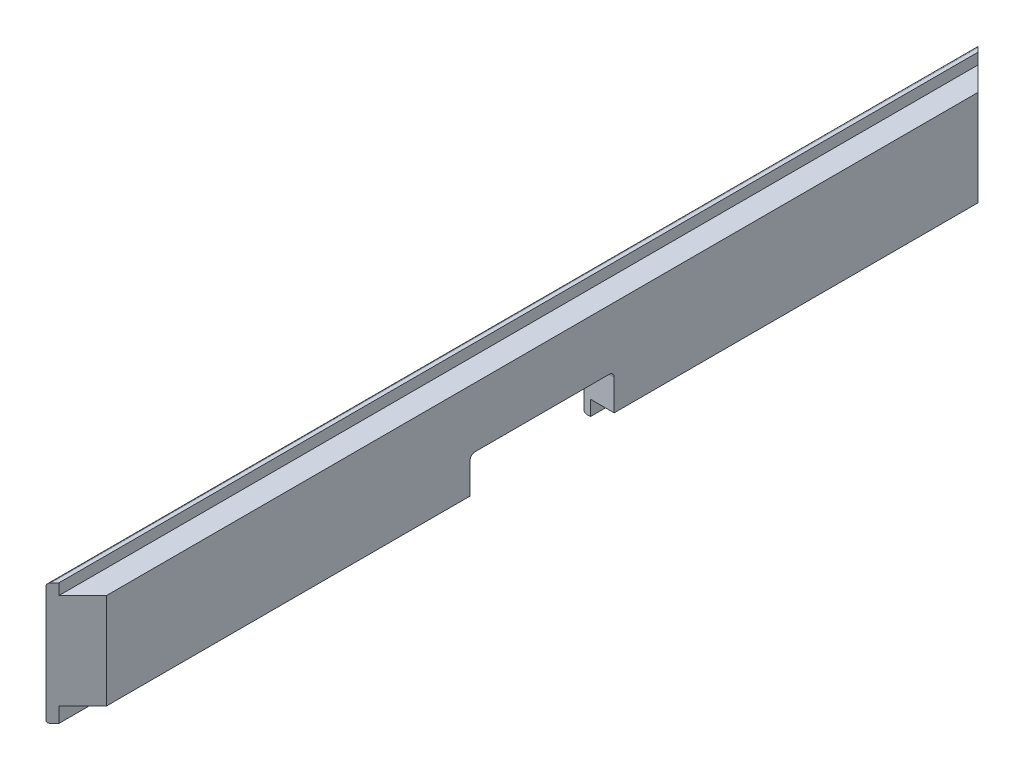
SolidWorks part; units mm, degrees
ref_plane "Front Plane" through (0, 0, 0) normal (0, 0, 1) x (1, 0, 0)
ref_plane "Top Plane" through (0, 0, 0) normal (0, 1, 0) x (1, 0, 0)
ref_plane "Right Plane" through (0, 0, 0) normal (1, 0, 0) x (0, 0, -1)
sketch "Sketch1" plane through (0, 0, 0) normal (0, 0, 1) x (1, 0, 0)
  line L1 (0, 0) -> (19.05, 0)
  line L2 (0, 0) -> (0, 77)
  line L3 (0, 77) -> (19.05, 77)
  line L4 (19.05, 0) -> (19.05, 77)
  line L5 (19.05, 77) -> (4.05, 77)
  line L6 (19.05, 77) -> (19.05, 70)
  line L7 (19.05, 70) -> (4.05, 70)
  line L8 (4.05, 77) -> (4.05, 70)
  line L9 (19.05, 0) -> (4.05, 0)
  line L10 (19.05, 0) -> (19.05, 9.525)
  line L11 (19.05, 9.525) -> (4.05, 9.525)
  line L12 (4.05, 0) -> (4.05, 9.525)
  dimension "D3" = 15
  dimension "D4" = 9.525
  dimension "D5" = 7
  dimension "D1" = 77
  dimension "D2" = 19.05
extrude "Boss-Extrude1" add sketch "Sketch1" along normal mid plane 589.1 contours L1 L12 L11 L4 L7 L8 L3 L2
fillet "Fillet1" radius 1.5875 2 edges at (0, 0, 0) (0, 77, 0)
sketch "Sketch2" plane through (0, 77, 0) normal (0, 1, 0) x (1, 0, 0)
  line L4 (0, 294.55) -> (19.05, 275.5)
  line L5 (19.05, 275.5) -> (19.05, 294.55)
  line L6 (19.05, 294.55) -> (0, 294.55)
  line L7 (-10.4775, 0) -> (10.4775, 0) construction
  line L9 (19.05, 275.5) -> (19.05, 294.55)
  line L13 (19.05, -294.55) -> (24.8228, -295)
  line L14 (19.05, -275.5) -> (19.05, -294.55)
  line L16 (19.05, -294.55) -> (0, -294.55)
  line L17 (19.05, -275.5) -> (19.05, -294.55)
  line L18 (0, -294.55) -> (19.05, -275.5)
  line L19 (19.05, -294.55) -> (19.05, 294.55) construction
extrude "Cut-Extrude1" cut sketch "Sketch2" against normal through all both and the other way through all
sketch "Sketch3" plane through (0, 9.525, 0) normal (0, -1, 0) x (1, 0, 0)
  line L0 (4.05, -260.5) -> (19.05, -260.5) construction
  line L1 (19.05, 275.5) -> (19.05, -275.5) construction
  line L2 (4.05, 290.5) -> (4.05, -290.5) construction
  line L3 (0, 0) -> (19.05, 0) construction
  line L4 (0, -294.55) -> (0, 294.55) construction
  line L5 (4.05, 260.5) -> (19.05, 260.5) construction
  point P0 (11.55, -260.5)
  point P6 (11.55, -260.5)
  point P10 (11.55, 260.5)
  dimension "D1" = 15
sketch "Sketch5" plane through (0, 0, 0) normal (0, 1, 0) x (1, 0, 0)
  line L0 (22.86, 294.55) -> (22.86, 219.55) construction
  line L1 (35.56, 294.55) -> (35.56, 219.55)
  line L2 (10.16, 294.55) -> (10.16, 219.55)
  line L5 (-10.4775, 0) -> (10.4775, 0) construction
  line L9 (19.05, -275.5) -> (19.05, 275.5) construction
  line L10 (22.86, -294.55) -> (22.86, -219.55) construction
  line L11 (35.56, -294.55) -> (35.56, -219.55)
  line L12 (10.16, -294.55) -> (10.16, -219.55)
  arc A0 (35.56, 294.55) -> (10.16, 294.55) centre (22.86, 294.55) ccw
  arc A1 (10.16, 219.55) -> (35.56, 219.55) centre (22.86, 219.55) ccw
  arc A4 (35.56, -294.55) -> (10.16, -294.55) centre (22.86, -294.55) cw
  arc A5 (10.16, -219.55) -> (35.56, -219.55) centre (22.86, -219.55) cw
  point P2 (22.86, 257.05)
  point P16 (22.86, -257.05)
  dimension "D1" = 25.4
  dimension "D2" = 75
  dimension "D3" = 3.81
extrude "Cut-Extrude2" [suppressed] cut sketch "Sketch5" along normal blind 25.4
sketch "Sketch6" plane through (0, 9.525, 0) normal (0, -1, 0) x (1, 0, 0)
  line L1 (10.4775, 0) -> (-10.4775, 0) construction
  line L7 (11.55, -209.1) -> (11.55, 0) construction
  line L8 (19.05, 275.5) -> (19.05, -275.5) construction
  line L9 (0, 0) -> (19.05, 0) construction
  point P4 (11.55, 104.55)
  point P14 (11.55, -104.55)
  dimension "D1" = 7.5
  dimension "D2" = 190
hole_wizard "Ø7.9 (7.9) Diameter Hole2" positions "Sketch6" profile "Sketch7" hole size "Ø7.9" standard "ISO"
sketch "Sketch7" plane through (11.55, 9.525, -104.55) normal (1, 0, 0) x (0, 0, -1)
  line L0 (0, 0) -> (0, 17.3734)
  line L1 (0, 17.3734) -> (3.95, 15)
  line L2 (3.95, 15) -> (3.95, 0)
  line L5 (3.95, 0) -> (0, 0)
  line L10 (0, 17.3734) -> (-3.95, 15) construction
  line L11 (0, -6.35) -> (0, 107.95) construction
  dimension "Hole Dia." = 7.9
  dimension "Hole Depth" = 15
  dimension "Drill Angle" = 118
sketch "Sketch8" plane through (0, 0, 0) normal (0, 0, 1) x (1, 0, 0)
  line L1 (0, 88.9) -> (19.05, 88.9)
  line L2 (0, 88.9) -> (0, 0)
  line L3 (0, 0) -> (19.05, 0)
  line L4 (19.05, 88.9) -> (19.05, 0)
  dimension "D1" = 19.05
  dimension "D2" = 88.9
sketch "Sketch9" plane through (0, 0, 0) normal (-1, 0, 0) x (0, 0, 1)
  line L0 (275.5, 9.525) -> (-275.5, 9.525) construction
  line L1 (-45.525, 32.215) -> (45.525, 32.215)
  line L2 (-45.525, 32.215) -> (-45.525, 7.215)
  line L3 (-45.525, 7.215) -> (45.525, 7.215)
  line L4 (45.525, 32.215) -> (45.525, 7.215)
  line L5 (-26.325, 27.015) -> (-19.125, 27.015) construction
  line L6 (-39.525, 27.015) -> (-32.325, 27.015) construction
  line L7 (-39.525, 27.015) -> (-39.525, 12.415) construction
  line L8 (-39.525, 12.415) -> (-32.325, 12.415) construction
  line L9 (-32.325, 27.015) -> (-32.325, 12.415) construction
  line L10 (-26.325, 27.015) -> (-26.325, 12.415) construction
  line L11 (-26.325, 12.415) -> (-19.125, 12.415) construction
  line L12 (-19.125, 27.015) -> (-19.125, 12.415) construction
  line L13 (-45.525, 19.715) -> (-39.525, 19.715) construction
  line L14 (-32.325, 19.715) -> (-26.325, 19.715) construction
  line L15 (39.525, 19.715) -> (45.525, 19.715) construction
  line L16 (292.9625, 0) -> (-292.9625, 0) construction
  line L17 (-45.525, 7.215) -> (45.525, 7.215)
  line L18 (-45.525, 7.215) -> (-45.525, 0)
  line L19 (-45.525, 0) -> (45.525, 0)
  line L20 (45.525, 7.215) -> (45.525, 0)
  circle A0 centre (34.525, 19.715) radius 5 construction
  point P4 (0, 7.215)
  line M5 (-294.55, 1.5875) -> (294.55, 1.5875)
  dimension "D8" = 10
  dimension "D1" = 14.6
  dimension "D2" = 91.05
  dimension "D3" = 25
  dimension "D4" = 22.69
  dimension "D5" = 7.2
  dimension "D7" = 6
extrude "Cut-Extrude3" cut sketch "Sketch9" against normal through all both and the other way through all contours L4 L1 L2 L3 | L20 L3 L18 M5 | L20 L18 L19 M5
fillet "Fillet2" radius 3.175 2 edges at (9.525, 32.215, -45.525) (9.525, 32.215, 45.525)
sketch "Sketch10" plane through (19.05, 0, 0) normal (1, 0, 0) x (0, 0, -1)
  line L0 (-275.5, 70) -> (275.5, 70) construction
  line L1 (-129.4969, 11.66) -> (-46.8669, 11.66)
  line L2 (-129.4969, 11.66) -> (-129.4969, 60)
  line L3 (-129.4969, 60) -> (-46.8669, 60)
  line L4 (-46.8669, 11.66) -> (-46.8669, 60)
  line L5 (-129.4969, 11.66) -> (-46.8669, 60) construction
  line L6 (-129.4969, 60) -> (-46.8669, 11.66) construction
  point P0 (-88.1819, 35.83)
  dimension "D1" = 48.34
  dimension "D2" = 82.63
  dimension "D3" = 10
sketch "Sketch11" plane through (19.05, 0, 0) normal (1, 0, 0) x (0, 0, -1)
  line L0 (-129.4969, 11.66) -> (-46.8669, 11.66) construction
  line L1 (-129.4969, 11.66) -> (-129.4969, 60) construction
  circle A0 centre (-129.4969, 60) radius 1.506
  circle A1 centre (-46.8669, 60) radius 1.506
  circle A2 centre (-122.0069, 11.66) radius 1.506
  circle A3 centre (-46.8669, 11.66) radius 1.506
  dimension "D1" = 3.012
  dimension "D2" = 7.49
equation "\"SquareSize\" = 5cm"
equation "\"TileCountX\"=12"
equation "\"TileCountY\"= 8"
equation "\"BottomBoardXSize\" = 880mm"
equation "\"BottomBoardYSize\" = 580mm"
equation "\"TopBoardXSize\" = 881mm"
equation "\"TopBoardYSize\"= 581mm"
equation "\"GantryHeight\"= 64mm"
equation "\"EncWallThickness\"= 5mm"
equation "\"EncLip\"= 15mm"
equation "\"TopBoardThickness\"= 3mm"
equation "\"BottomBoardThickness\"= .375in"
equation "\"D3@Sketch1\"=\"EncLip\""
equation "\"D4@Sketch1\"=\"BottomBoardThickness\""
equation "\"D5@Sketch1\"=7mm"
equation "\"D1@Boss-Extrude1\"=581mm+2*4.05000000"
equation "\"D1@Sketch6\"=\"EncLip\"/2"
equation "\"D1@Sketch1\"=\"GantryHeight\"+\"TopBoardThickness\"+10mm"
